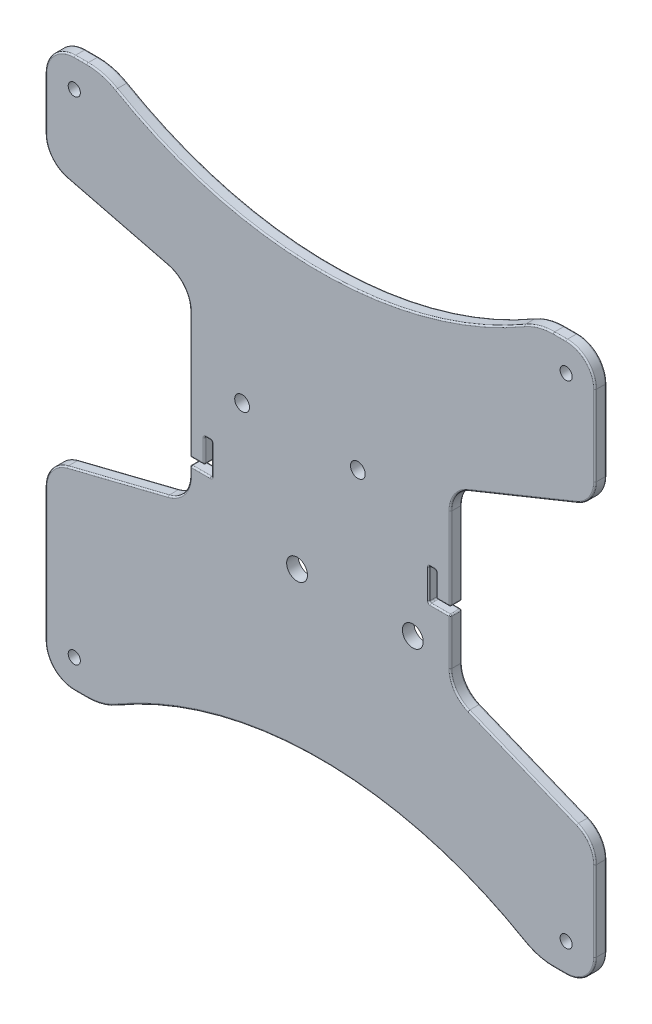
SolidWorks part; units mm, degrees
ref_plane "Alzado" through (0, 0, 0) normal (0, 0, 1) x (1, 0, 0)
ref_plane "Planta" through (0, 0, 0) normal (0, 1, 0) x (1, 0, 0)
ref_plane "Vista lateral" through (0, 0, 0) normal (1, 0, 0) x (0, 0, -1)
ref_plane "Plano1" through (0, 0, 0) normal (0, 0, -1) x (-1, 0, 0)
sketch "Croquis1" plane through (0, 0, 0) normal (0, 0, -1) x (-1, 0, 0)
  line L0 (87.4254, -29.1063) -> (52.5746, -20.3937)
  line L1 (45, -10.6922) -> (45, -8)
  line L2 (44.5, -7.5) -> (38, -7.5)
  line L3 (37.5, -7) -> (37.5, 3)
  line L4 (38, 3.5) -> (39.5, 3.5)
  line L5 (40, 3) -> (40, -4.5)
  line L6 (40.5, -5) -> (44.5, -5)
  line L7 (45, -4.5) -> (45, 38.6922)
  line L8 (52.5746, 48.3937) -> (87.4254, 57.1063)
  line L9 (95, 66.8078) -> (95, 85)
  line L10 (85, 95) -> (80.6, 95)
  line L11 (-80.6, 95) -> (-85, 95)
  line L12 (-95, 85) -> (-95, 57.3099)
  line L13 (-88.7544, 48.0415) -> (-51.2456, 32.8477)
  line L14 (-45, 23.5792) -> (-45, -4.5)
  line L15 (-44.5, -5) -> (-40.5, -5)
  line L16 (-40, -4.5) -> (-40, 3)
  line L17 (-39.5, 3.5) -> (-38, 3.5)
  line L18 (-37.5, 3) -> (-37.5, -7)
  line L19 (-38, -7.5) -> (-44.5, -7.5)
  line L20 (-45, -8) -> (-45, -23.5792)
  line L21 (-51.2456, -32.8477) -> (-88.7544, -48.0415)
  line L22 (-95, -57.3099) -> (-95, -85)
  line L23 (-85, -95) -> (-80.6, -95)
  line L24 (80.6, -95) -> (85, -95)
  line L25 (95, -85) -> (95, -38.8078)
  circle A0 centre (-85, -85) radius 2.1
  circle A1 centre (-85, 85) radius 2.1
  circle A2 centre (85, 85) radius 2.1
  circle A3 centre (85, -85) radius 2.1
  circle A4 centre (27, 20.1) radius 2.55
  circle A5 centre (8, -20.1) radius 3.6
  circle A6 centre (-32, -20.1) radius 3.6
  circle A7 centre (-13, 20.1) radius 2.55
  arc A8 (52.5746, -20.3937) -> (45, -10.6922) centre (55, -10.6922) cw
  arc A9 (45, -8) -> (44.5, -7.5) centre (44.5, -8) ccw
  arc A10 (38, -7.5) -> (37.5, -7) centre (38, -7) cw
  arc A11 (37.5, 3) -> (38, 3.5) centre (38, 3) cw
  arc A12 (39.5, 3.5) -> (40, 3) centre (39.5, 3) cw
  arc A13 (40, -4.5) -> (40.5, -5) centre (40.5, -4.5) ccw
  arc A14 (44.5, -5) -> (45, -4.5) centre (44.5, -4.5) ccw
  arc A15 (45, 38.6922) -> (52.5746, 48.3937) centre (55, 38.6922) cw
  arc A16 (87.4254, 57.1063) -> (95, 66.8078) centre (85, 66.8078) ccw
  arc A17 (95, 85) -> (85, 95) centre (85, 85) ccw
  arc A18 (80.6, 95) -> (70.525, 92.277) centre (80.6, 75) ccw
  arc A19 (70.525, 92.277) -> (-70.525, 92.277) centre (0, 213.2159) cw
  arc A20 (-70.525, 92.277) -> (-80.6, 95) centre (-80.6, 75) ccw
  arc A21 (-85, 95) -> (-95, 85) centre (-85, 85) ccw
  arc A22 (-95, 57.3099) -> (-88.7544, 48.0415) centre (-85, 57.3099) ccw
  arc A23 (-51.2456, 32.8477) -> (-45, 23.5792) centre (-55, 23.5792) cw
  arc A24 (-45, -4.5) -> (-44.5, -5) centre (-44.5, -4.5) ccw
  arc A25 (-40.5, -5) -> (-40, -4.5) centre (-40.5, -4.5) ccw
  arc A26 (-40, 3) -> (-39.5, 3.5) centre (-39.5, 3) cw
  arc A27 (-38, 3.5) -> (-37.5, 3) centre (-38, 3) cw
  arc A28 (-37.5, -7) -> (-38, -7.5) centre (-38, -7) cw
  arc A29 (-44.5, -7.5) -> (-45, -8) centre (-44.5, -8) ccw
  arc A30 (-45, -23.5792) -> (-51.2456, -32.8477) centre (-55, -23.5792) cw
  arc A31 (-88.7544, -48.0415) -> (-95, -57.3099) centre (-85, -57.3099) ccw
  arc A32 (-95, -85) -> (-85, -95) centre (-85, -85) ccw
  arc A33 (-80.6, -95) -> (-70.525, -92.277) centre (-80.6, -75) ccw
  arc A34 (-70.525, -92.277) -> (70.525, -92.277) centre (0, -213.2159) cw
  arc A35 (70.525, -92.277) -> (80.6, -95) centre (80.6, -75) ccw
  arc A36 (85, -95) -> (95, -85) centre (85, -85) ccw
  arc A37 (95, -38.8078) -> (87.4254, -29.1063) centre (85, -38.8078) ccw
extrude "Saliente-Extruir1" add sketch "Croquis1" against normal blind 4
fillet "Redondeo1" radius 0.5 112 edges at (-75.3818, 94.3072, 4) (-82.8, 95, 4) (-92.0711, 92.0711, 4) (-95, 75.9039, 4) (-92.8821, 60.6536, 4) (-70, 52.75, 4) (-47.1179, 44.8464, 4) (-45, 17.0961, 4) (-44.8536, -4.8536, 4) (-42.5, -5, 4) (-40.1464, -4.8536, 4) (-40, -0.75, 4) (-39.8536, 3.3536, 4) (-38.75, 3.5, 4) (-37.6464, 3.3536, 4) (-37.5, -2, 4) (-37.6464, -7.3536, 4) (-41.25, -7.5, 4) (-44.8536, -7.6464, 4) (-45, -9.3461, 4) (-47.1179, -16.8464, 4) (-70, -24.75, 4) (-92.8821, -32.6536, 4) (-95, -61.9039, 4) (-92.0711, -92.0711, 4) (-82.8, -95, 4) (-75.3818, -94.3072, 4) (0, -73.2159, 4) (75.3818, -94.3072, 4) (82.8, -95, 4) (92.0711, -92.0711, 4) (95, -71.155, 4) (93.2929, -51.7217, 4) (70, -40.4446, 4) (46.7071, -29.1674, 4) (45, -15.7896, 4) (44.8536, -7.6464, 4) (41.25, -7.5, 4) (37.6464, -7.3536, 4) (37.5, -2, 4) (37.6464, 3.3536, 4) (38.75, 3.5, 4) (39.8536, 3.3536, 4) (40, -0.75, 4) (40.1464, -4.8536, 4) (42.5, -5, 4) (44.8536, -4.8536, 4) (45, 9.5396, 4) (46.7071, 29.1674, 4) (70, 40.4446, 4) (93.2929, 51.7217, 4) (95, 71.155, 4) (92.0711, 92.0711, 4) (82.8, 95, 4) (75.3818, 94.3072, 4) (-75.3818, 94.3072, 0) (-82.8, 95, 0) (-92.0711, 92.0711, 0) (-95, 75.9039, 0) (-92.8821, 60.6536, 0) (-70, 52.75, 0) (-47.1179, 44.8464, 0) (-45, 17.0961, 0) (-44.8536, -4.8536, 0) (-42.5, -5, 0) (-40.1464, -4.8536, 0) (-40, -0.75, 0) (-39.8536, 3.3536, 0) (-38.75, 3.5, 0) (-37.6464, 3.3536, 0) (-37.5, -2, 0) (-37.6464, -7.3536, 0) (-41.25, -7.5, 0) (-44.8536, -7.6464, 0) (-45, -9.3461, 0) (-47.1179, -16.8464, 0) (-70, -24.75, 0) (-92.8821, -32.6536, 0) (-95, -61.9039, 0) (-92.0711, -92.0711, 0) (-82.8, -95, 0) (-75.3818, -94.3072, 0) (0, -73.2159, 0) (75.3818, -94.3072, 0) (82.8, -95, 0) (92.0711, -92.0711, 0) (95, -71.155, 0) (93.2929, -51.7217, 0) (70, -40.4446, 0) (46.7071, -29.1674, 0) (45, -15.7896, 0) (44.8536, -7.6464, 0) (41.25, -7.5, 0) (37.6464, -7.3536, 0) (37.5, -2, 0) (37.6464, 3.3536, 0) (38.75, 3.5, 0) (39.8536, 3.3536, 0) (40, -0.75, 0) (40.1464, -4.8536, 0) (42.5, -5, 0) (44.8536, -4.8536, 0) (45, 9.5396, 0) (46.7071, 29.1674, 0) (70, 40.4446, 0) (93.2929, 51.7217, 0) (95, 71.155, 0) (92.0711, 92.0711, 0) (82.8, 95, 0) (75.3818, 94.3072, 0) (0, 73.2159, 4) (0, 73.2159, 0)
